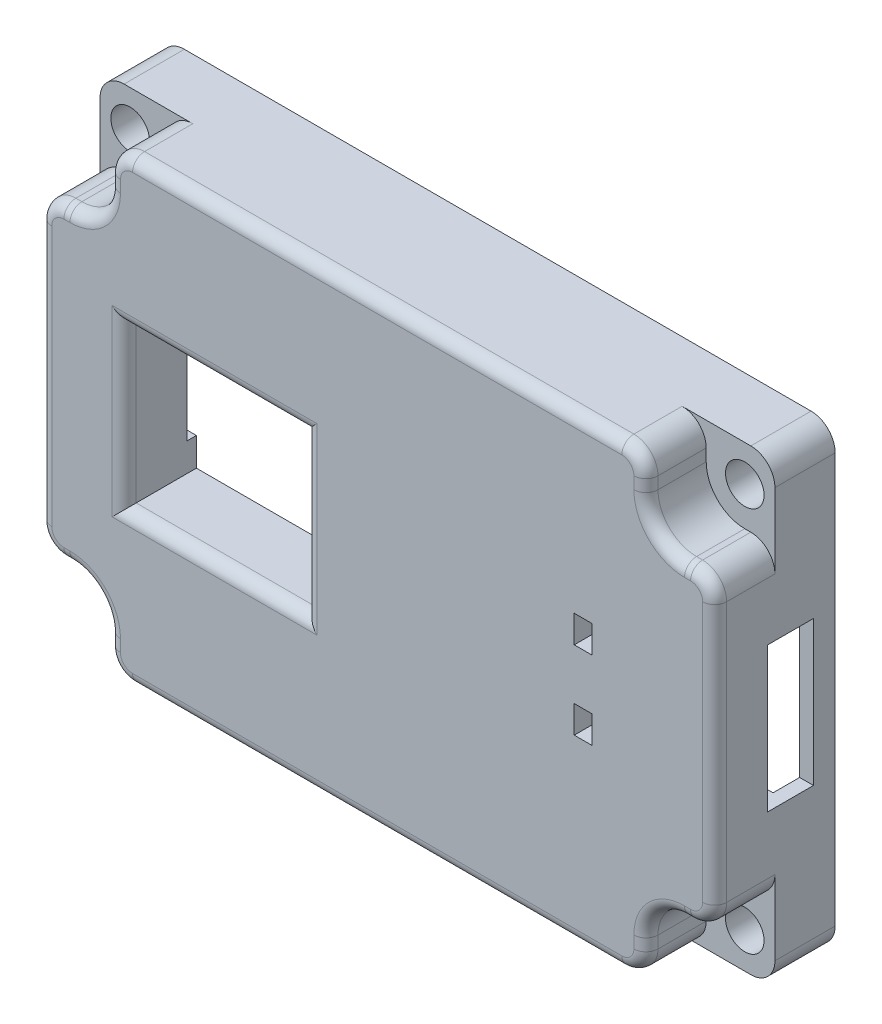
SolidWorks part; units mm, degrees
ref_plane "前视基准面" through (0, 0, 0) normal (0, 0, 1) x (1, 0, 0)
ref_plane "上视基准面" through (0, 0, 0) normal (0, 1, 0) x (1, 0, 0)
ref_plane "右视基准面" through (0, 0, 0) normal (1, 0, 0) x (0, 0, -1)
sketch "草图1" plane through (0, 0, 0) normal (0, 0, 1) x (1, 0, 0)
  line L1 (-28, -19) -> (28, -19)
  line L2 (-28, -19) -> (-28, 19)
  line L3 (-28, 19) -> (28, 19)
  line L4 (28, -19) -> (28, 19)
  line L5 (-28, -19) -> (28, 19) construction
  line L6 (-28, 19) -> (28, -19) construction
  point P0 (0, 0)
  dimension "D1" = 38
  dimension "D2" = 56
extrude "凸台-拉伸1" add sketch "草图1" along normal blind 10
sketch "草图2" plane through (0, 0, 10) normal (0, 0, 1) x (1, 0, 0)
  line L0 (-28, 19) -> (-28, -19) construction
  line L1 (-21, 6.6) -> (-6, 6.6)
  line L2 (-21, 6.6) -> (-21, -6.6)
  line L3 (-21, -6.6) -> (-6, -6.6)
  line L4 (-6, 6.6) -> (-6, -6.6)
  line L5 (-21, 6.6) -> (-6, -6.6) construction
  line L6 (-21, -6.6) -> (-6, 6.6) construction
  line L9 (16.35, 4.65) -> (17.83, 4.65)
  line L10 (16.35, 4.65) -> (16.35, 2.38)
  line L11 (16.35, 2.38) -> (17.83, 2.38)
  line L12 (17.83, 4.65) -> (17.83, 2.38)
  line L13 (16.35, 4.65) -> (17.83, 2.38) construction
  line L14 (16.35, 2.38) -> (17.83, 4.65) construction
  line L15 (16.35, -1.84) -> (17.83, -1.84)
  line L16 (16.35, -1.84) -> (16.35, -4.11)
  line L17 (16.35, -4.11) -> (17.83, -4.11)
  line L18 (17.83, -1.84) -> (17.83, -4.11)
  line L19 (16.35, -1.84) -> (17.83, -4.11) construction
  line L20 (16.35, -4.11) -> (17.83, -1.84) construction
  point P0 (-13.5, 0)
  point P10 (17.09, 3.515)
  point P15 (17.09, -2.975)
  dimension "D1" = 13.2
  dimension "D2" = 15
  dimension "D3" = 7
  dimension "D5" = 22.35
  dimension "D6" = 1.48
  dimension "D7" = 2.27
  dimension "D8" = 1.48
  dimension "D9" = 2.27
  dimension "D10" = 1.95
  dimension "D11" = 4.22
extrude "切除-拉伸1" cut sketch "草图2" against normal blind 8
sketch "草图3" plane through (0, 0, 0) normal (0, 0, -1) x (-1, 0, 0)
  line L1 (-26.85, 11.35) -> (26.85, 11.35)
  line L2 (-26.85, 11.35) -> (-26.85, -11.35)
  line L3 (-26.85, -11.35) -> (26.85, -11.35)
  line L4 (26.85, 11.35) -> (26.85, -11.35)
  line L5 (-26.85, 11.35) -> (26.85, -11.35) construction
  line L6 (-26.85, -11.35) -> (26.85, 11.35) construction
  point P0 (0, 0)
  dimension "D1" = 53.7
  dimension "D2" = 22.7
extrude "切除-拉伸2" cut sketch "草图3" against normal blind 2
sketch "草图5" plane through (-28, 0, 0) normal (-1, 0, 0) x (0, 0, 1)
  line L1 (4.78, -4.25) -> (1.58, -4.25)
  line L2 (4.78, -4.25) -> (4.78, 4.25)
  line L3 (4.78, 4.25) -> (1.58, 4.25)
  line L4 (1.58, -4.25) -> (1.58, 4.25)
  line L5 (4.78, -4.25) -> (1.58, 4.25) construction
  line L6 (4.78, 4.25) -> (1.58, -4.25) construction
  line L7 (10, 19) -> (10, -19) construction
  point P0 (3.18, 0)
  dimension "D1" = 3.2
  dimension "D2" = 8.5
  dimension "D3" = 5.22
extrude "切除-拉伸4" cut sketch "草图5" against normal up to next
sketch "草图6" plane through (28, 0, 0) normal (1, 0, 0) x (0, 0, -1)
  line L0 (-10, -19) -> (-10, 19) construction
  line L1 (-5.6, -6) -> (-1.8, -6)
  line L2 (-5.6, -6) -> (-5.6, 6)
  line L3 (-5.6, 6) -> (-1.8, 6)
  line L4 (-1.8, -6) -> (-1.8, 6)
  line L5 (-5.6, -6) -> (-1.8, 6) construction
  line L6 (-5.6, 6) -> (-1.8, -6) construction
  point P0 (-3.7, 0)
  dimension "D1" = 12
  dimension "D2" = 3.8
  dimension "D3" = 4.4
extrude "切除-拉伸5" cut sketch "草图6" against normal up to next
sketch "草图7" plane through (0, 0, 0) normal (0, 0, -1) x (-1, 0, 0)
  line L0 (-28, 19) -> (28, 19) construction
  line L1 (28, 19) -> (28, -19) construction
  line L2 (-28, 0) -> (28, 0) construction
  line L3 (-28, -19) -> (-28, 19) construction
  line L4 (0, 19) -> (0, -19) construction
  line L5 (28, -19) -> (-28, -19) construction
  circle A0 centre (25.5, 16) radius 1.6
  circle A1 centre (25.5, -16) radius 1.6
  circle A2 centre (-25.5, -16) radius 1.6
  circle A3 centre (-25.5, 16) radius 1.6
  dimension "D1" = 3.2
  dimension "D2" = 3
  dimension "D3" = 2.5
extrude "切除-拉伸6" cut sketch "草图7" against normal through all
fillet "圆角1" radius 2 4 edges at (-28, 19, 5) (28, 19, 5) (-28, -19, 5) (28, -19, 5)
sketch "草图8" plane through (0, 0, 10) normal (0, 0, 1) x (1, 0, 0)
  line L0 (-28, 0) -> (28, 0) construction
  line L1 (-28, 17) -> (-28, -17) construction
  line L2 (28, -17) -> (28, 17) construction
  line L3 (0, -19) -> (0, 19) construction
  line L4 (-26, -19) -> (26, -19) construction
  line L5 (26, 19) -> (-26, 19) construction
  line L6 (-22.3, 16) -> (-22.3, 19)
  line L7 (-25.5, 12.8) -> (-28, 12.8)
  line L8 (-26, 19) -> (-22.3, 19)
  line L9 (-28, 12.8) -> (-28, 17)
  line L10 (28, 12.8) -> (28, 17)
  line L11 (25.5, 12.8) -> (28, 12.8)
  line L12 (22.3, 16) -> (22.3, 19)
  line L13 (26, 19) -> (22.3, 19)
  line L14 (-28, -12.8) -> (-28, -17)
  line L15 (-25.5, -12.8) -> (-28, -12.8)
  line L16 (-22.3, -16) -> (-22.3, -19)
  line L17 (-26, -19) -> (-22.3, -19)
  line L18 (26, -19) -> (22.3, -19)
  line L19 (22.3, -16) -> (22.3, -19)
  line L20 (25.5, -12.8) -> (28, -12.8)
  line L21 (28, -12.8) -> (28, -17)
  arc A1 (-26, 19) -> (-28, 17) centre (-26, 17) ccw
  arc A2 (-25.5, 12.8) -> (-22.3, 16) centre (-25.5, 16) ccw
  arc A3 (26, 19) -> (28, 17) centre (26, 17) cw
  arc A4 (25.5, 12.8) -> (22.3, 16) centre (25.5, 16) cw
  arc A5 (-26, -19) -> (-28, -17) centre (-26, -17) cw
  arc A6 (-25.5, -12.8) -> (-22.3, -16) centre (-25.5, -16) cw
  arc A7 (25.5, -12.8) -> (22.3, -16) centre (25.5, -16) ccw
  arc A8 (26, -19) -> (28, -17) centre (26, -17) ccw
  dimension "D1" = 3.2
extrude "切除-拉伸7" cut sketch "草图8" against normal blind 5
fillet "圆角3" radius 2 8 edges at (22.3, -19, 7.5) (28, -12.8, 7.5) (22.3, 19, 7.5) (28, 12.8, 7.5) (-22.3, 19, 7.5) (-28, 12.8, 7.5) (-22.3, -19, 7.5) (-28, -12.8, 7.5)
fillet "圆角4" radius 1 28 edges at (-22.3, -16.5, 10) (-21.7142, -18.4142, 10) (0, -19, 10) (21.7142, -18.4142, 10) (22.3, -16.5, 10) (23.2373, -13.7373, 10) (25.75, -12.8, 10) (27.4142, -12.2142, 10) (28, 0, 10) (27.4142, 12.2142, 10) (25.75, 12.8, 10) (23.2373, 13.7373, 10) (22.3, 16.5, 10) (21.7142, 18.4142, 10) (0, 19, 10) (-21.7142, 18.4142, 10) (-22.3, 16.5, 10) (-23.2373, 13.7373, 10) (-25.75, 12.8, 10) (-27.4142, 12.2142, 10) (-28, 0, 10) (-27.4142, -12.2142, 10) (-25.75, -12.8, 10) (-13.5, -6.6, 10) (-21, 0, 10) (-6, 0, 10) (-13.5, 6.6, 10) (-23.2373, -13.7373, 10)
sketch "草图10" plane through (0, 0, 0) normal (0, 0, -1) x (-1, 0, 0)
  line L0 (26.85, 4.25) -> (26.85, 11.35) construction
  line L1 (-26.85, -9) -> (26.85, -9)
  line L2 (-26.85, -9) -> (-26.85, 9)
  line L3 (-26.85, 9) -> (26.85, 9)
  line L4 (26.85, -9) -> (26.85, 9)
  line L5 (-26.85, -9) -> (26.85, 9) construction
  line L6 (-26.85, 9) -> (26.85, -9) construction
  point P0 (0, 0)
  dimension "D1" = 18
extrude "切除-拉伸9" cut sketch "草图10" against normal blind 4
